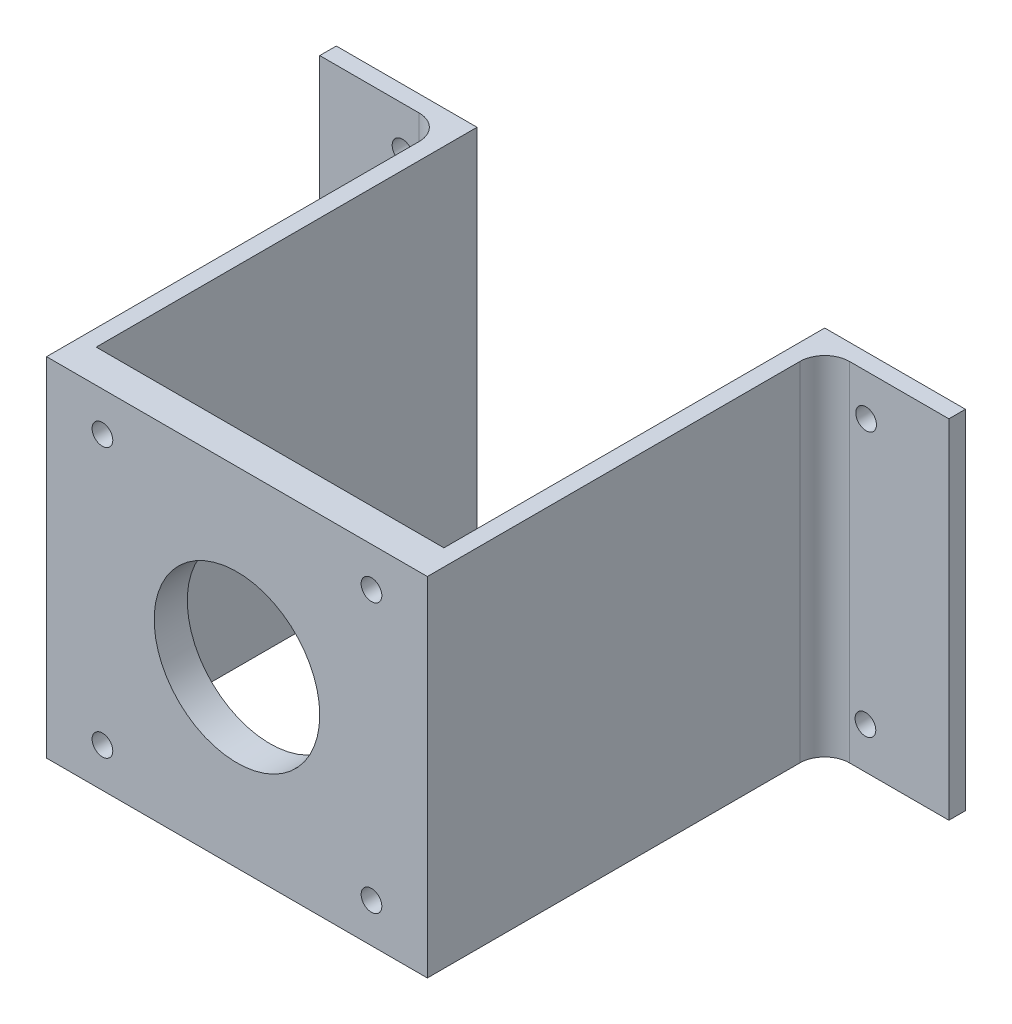
SolidWorks part; units mm, degrees
ref_plane "Alzado" through (0, 0, 0) normal (0, 0, 1) x (1, 0, 0)
ref_plane "Planta" through (0, 0, 0) normal (0, 1, 0) x (1, 0, 0)
ref_plane "Vista lateral" through (0, 0, 0) normal (1, 0, 0) x (0, 0, -1)
sketch "Croquis1" plane through (0, 0, 0) normal (0, 0, 1) x (1, 0, 0)
  line L1 (-84.7498, 36.6204) -> (-38.7498, 36.6204)
  line L2 (-84.7498, 36.6204) -> (-84.7498, -5.3796)
  line L3 (-84.7498, -5.3796) -> (-38.7498, -5.3796)
  line L4 (-38.7498, 36.6204) -> (-38.7498, -5.3796)
  line L5 (-84.7498, 36.6204) -> (-38.7498, -5.3796) construction
  line L6 (-84.7498, -5.3796) -> (-38.7498, 36.6204) construction
  point P0 (-61.7498, 15.6204)
  dimension "D1" = 46
extrude "Saliente-Extruir1" add sketch "Croquis1" along normal blind 4
sketch "Croquis3" plane through (0, 0, 0) normal (0, 0, -1) x (-1, 0, 0)
  line L0 (82.7498, 36.6204) -> (84.7498, 36.6204)
  line L1 (38.7498, 36.6204) -> (84.7498, 36.6204) construction
  line L2 (82.7498, 36.6204) -> (82.7498, -5.3796)
  line L3 (84.7498, -5.3796) -> (38.7498, -5.3796) construction
  line L4 (82.7498, -5.3796) -> (84.7498, -5.3796)
  line L5 (84.7498, 36.6204) -> (84.7498, -5.3796)
  line L6 (38.7498, 36.6204) -> (40.7498, 36.6204)
  line L7 (38.7498, 36.6204) -> (38.7498, -5.3796)
  line L8 (38.7498, -5.3796) -> (38.7498, 36.6204) construction
  line L9 (40.7498, 36.6204) -> (40.7498, -5.3796)
  line L10 (38.7498, -5.3796) -> (40.7498, -5.3796)
extrude "Saliente-Extruir2" add sketch "Croquis3" along normal blind 46
sketch "Croquis4" plane through (-84.7498, 0, 0) normal (-1, 0, 0) x (0, 0, 1)
  line L0 (-46, 36.6204) -> (-44, 36.6204)
  line L1 (4, 36.6204) -> (-46, 36.6204) construction
  line L2 (-44, 36.6204) -> (-44, -5.3796)
  line L3 (4, -5.3796) -> (-46, -5.3796) construction
  line L4 (-44, -5.3796) -> (-46, -5.3796)
  line L5 (-46, -5.3796) -> (-46, 36.6204)
extrude "Saliente-Extruir3" add sketch "Croquis4" along normal blind 15 contours L5 L0 L2 L4
sketch "Croquis6" plane through (-38.7498, 0, 0) normal (1, 0, 0) x (0, 0, -1)
  line L0 (46, 36.6204) -> (44, 36.6204)
  line L1 (-4, 36.6204) -> (46, 36.6204) construction
  line L2 (44, 36.6204) -> (44, -5.3796)
  line L3 (-4, -5.3796) -> (46, -5.3796) construction
  line L4 (44, -5.3796) -> (46, -5.3796)
  line L5 (46, -5.3796) -> (46, 36.6204)
extrude "Saliente-Extruir4" add sketch "Croquis6" along normal blind 15
sketch "Croquis7" plane through (0, 0, 4) normal (0, 0, 1) x (1, 0, 0)
  line L0 (-38.7498, -5.3796) -> (-45.4998, -5.3796)
  line L1 (-84.7498, -5.3796) -> (-38.7498, -5.3796) construction
  line L2 (-45.4998, -5.3796) -> (-45.4998, -0.6296)
  line L3 (-45.4998, -0.6296) -> (-38.7498, -0.6296)
  line L4 (-38.7498, -5.3796) -> (-38.7498, 36.6204) construction
  line L5 (-38.7498, -0.6296) -> (-38.7498, -5.3796)
  circle A0 centre (-45.4998, -0.6296) radius 1.25
  point P10 (0, 0)
  dimension "D1" = 2.5
  dimension "D2" = 6.75
sketch "Croquis8" plane through (0, 0, 4) normal (0, 0, 1) x (1, 0, 0)
  line L0 (-84.7498, -5.3796) -> (-77.9998, -5.3796)
  line L1 (-84.7498, -5.3796) -> (-38.7498, -5.3796) construction
  line L2 (-77.9998, -5.3796) -> (-77.9998, -0.6296)
  line L3 (-77.9998, -0.6296) -> (-84.7498, -0.6296)
  line L4 (-84.7498, 36.6204) -> (-84.7498, -5.3796) construction
  line L5 (-84.7498, -0.6296) -> (-84.7498, -5.3796)
  line L6 (-84.7498, 36.6204) -> (-84.7498, 31.8704)
  line L7 (-84.7498, 36.6204) -> (-84.7498, -5.3796) construction
  line L8 (-84.7498, 31.8704) -> (-77.9998, 31.8704)
  line L9 (-77.9998, 31.8704) -> (-77.9998, 36.6204)
  line L10 (-38.7498, 36.6204) -> (-84.7498, 36.6204) construction
  line L11 (-77.9998, 36.6204) -> (-84.7498, 36.6204)
  line L12 (-38.7498, 36.6204) -> (-38.7498, 31.8704)
  line L13 (-38.7498, -5.3796) -> (-38.7498, 36.6204) construction
  line L14 (-38.7498, 36.6204) -> (-45.4998, 36.6204)
  line L15 (-45.4998, 36.6204) -> (-45.4998, 31.8704) construction
  line L16 (-45.4998, 31.8704) -> (-38.7498, 31.8704) construction
  circle A0 centre (-45.4998, 31.8704) radius 1.25
  circle A1 centre (-77.9998, 31.8704) radius 1.25
  circle A2 centre (-77.9998, -0.6296) radius 1.25
  dimension "D1" = 2.5
  dimension "D2" = 2.5
  dimension "D3" = 2.5
sketch "Croquis9" plane through (0, 0, 4) normal (0, 0, 1) x (1, 0, 0)
extrude "Cortar-Extruir1" cut sketch "Croquis8" against normal blind 15 contours A0 | L2 A2 L3 | L3 A2 L2 | A1
extrude "Cortar-Extruir2" cut sketch "Croquis7" against normal blind 15 contours L3 A0 L2 | L2 A0 L3
sketch "Croquis10" plane through (0, 0, -44) normal (0, 0, 1) x (1, 0, 0)
  line L0 (-23.7498, 36.6204) -> (-38.7498, 36.6204) construction
  line L1 (-33.8299, -0.3796) -> (-33.7498, -5.3796) construction
  line L2 (-23.7498, -5.3796) -> (-38.7498, -5.3796) construction
  line L3 (-33.7498, -5.3796) -> (-38.7498, -5.3796) construction
  line L10 (-38.7498, -5.3796) -> (-38.7498, -0.3796) construction
  line L11 (-38.7498, 36.6204) -> (-38.7498, -5.3796) construction
  line L12 (-38.7498, -0.3796) -> (-33.8299, -0.3796) construction
  circle A0 centre (-33.7498, 31.6204) radius 1.25
  circle A3 centre (-33.8299, -0.3796) radius 1.25
  dimension "D5" = 2.5
  dimension "D4" = 2.5
  dimension "D1" = 15
  dimension "D2" = 5
  dimension "D3" = 5
extrude "Cortar-Extruir4" cut sketch "Croquis10" against normal blind 15 contours A0
ref_plane "Plano4" through (-61.7498, 0, 0) normal (1, 0, 0) x (0, 0, -1)
mirror "Simetría1" about plane through (-61.7498, 0, 0) normal (1, 0, 0) of "Cortar-Extruir4"
fillet "Redondeo1" radius 3 1 edges at (-84.7498, 15.6204, -44)
fillet "Redondeo2" radius 3 1 edges at (-38.7498, 15.6204, -44)
sketch "Croquis11" plane through (0, 0, 4) normal (0, 0, 1) x (1, 0, 0)
  line L0 (-84.7498, 15.6204) -> (-38.7498, 15.6204) construction
  line L1 (-84.7498, 36.6204) -> (-84.7498, -5.3796) construction
  line L2 (-38.7498, -5.3796) -> (-38.7498, 36.6204) construction
  line L3 (-61.7498, 36.6204) -> (-61.7498, -5.2663) construction
  line L4 (-38.7498, 36.6204) -> (-84.7498, 36.6204) construction
  line L5 (-61.7498, -23.1) -> (-61.7498, 23.1) construction
  circle A0 centre (-61.7498, 15.6204) radius 10
  dimension "D1" = 20
extrude "Cortar-Extruir5" cut sketch "Croquis11" against normal blind 15
